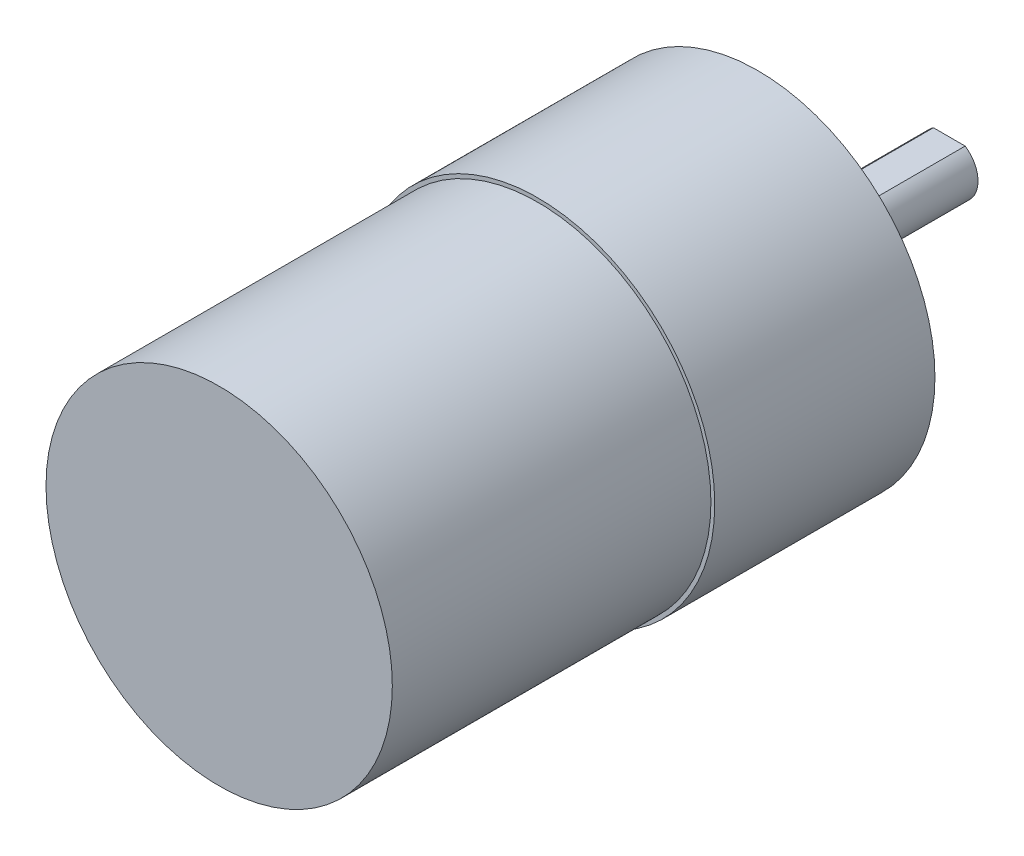
SolidWorks part; units mm, degrees
ref_plane "Front Plane" through (0, 0, 0) normal (0, 0, 1) x (1, 0, 0)
ref_plane "Top Plane" through (0, 0, 0) normal (0, 1, 0) x (1, 0, 0)
ref_plane "Right Plane" through (0, 0, 0) normal (1, 0, 0) x (0, 0, -1)
sketch "Sketch1" plane through (0, 0, 0) normal (0, 0, 1) x (1, 0, 0)
  circle A0 centre (0, 0) radius 18.5
  dimension "D1" = 37
extrude "Boss-Extrude1" add sketch "Sketch1" along normal blind 23.0162
sketch "Sketch2" plane through (0, 0, 23.0162) normal (0, 0, 1) x (1, 0, 0)
  circle A0 centre (0, 0) radius 18.1
  dimension "D1" = 36.2
extrude "Boss-Extrude2" add sketch "Sketch2" along normal blind 33.3
sketch "Sketch3" plane through (0, 0, 0) normal (0, 0, -1) x (-1, 0, 0)
  circle A0 centre (0, 0) radius 6
  dimension "D2" = 12
  dimension "D1" = 0
extrude "Boss-Extrude3" add sketch "Sketch3" along normal blind 5
sketch "Sketch4" plane through (0, 0, -5) normal (0, 0, -1) x (-1, 0, 0)
  arc A0 (-0.5159, 2.9553) -> (0.5159, 2.9553) centre (0, 0) ccw
  arc A1 (-0.5159, 2.9553) -> (0.5159, 2.9553) centre (0, 0) cw
  dimension "D1" = 6
extrude "Boss-Extrude4" add sketch "Sketch4" along normal blind 15
sketch "Sketch5" plane through (0, 0, -20) normal (0, 0, -1) x (-1, 0, 0)
  line L0 (-1.6583, 2.5) -> (1.6583, 2.5)
  line L1 (0, 2.5) -> (0, -3) construction
  circle A0 centre (0, 0) radius 3 construction
  circle A1 centre (0, 0) radius 3 construction
  arc A2 (1.6583, 2.5) -> (-1.6583, 2.5) centre (0, 0) ccw
  dimension "D1" = 5.5
extrude "Cut-Extrude1" cut sketch "Sketch5" against normal blind 14
sketch "Sketch6" plane through (0, 0, 0) normal (0, 0, -1) x (-1, 0, 0)
  line L0 (0, 0) -> (0, 15.5) construction
  line L1 (7.75, 13.4234) -> (0, 0) construction
  circle A0 centre (0, 0) radius 15.5 construction
  circle A2 centre (7.75, 13.4234) radius 1.5
  circle A3 centre (15.5, 0) radius 1.5
  circle A4 centre (7.75, -13.4234) radius 1.5
  circle A5 centre (-7.75, -13.4234) radius 1.5
  circle A6 centre (-15.5, 0) radius 1.5
  circle A7 centre (-7.75, 13.4234) radius 1.5
  point P3 (7.75, 13.4234)
  point P14 (0, 0)
  point P21 (0, 0)
  dimension "D1" = 31
  dimension "D3" = 3
  dimension "D2" = 30
  dimension "D4" = 6
extrude "Cut-Extrude2" cut sketch "Sketch6" against normal blind 8
